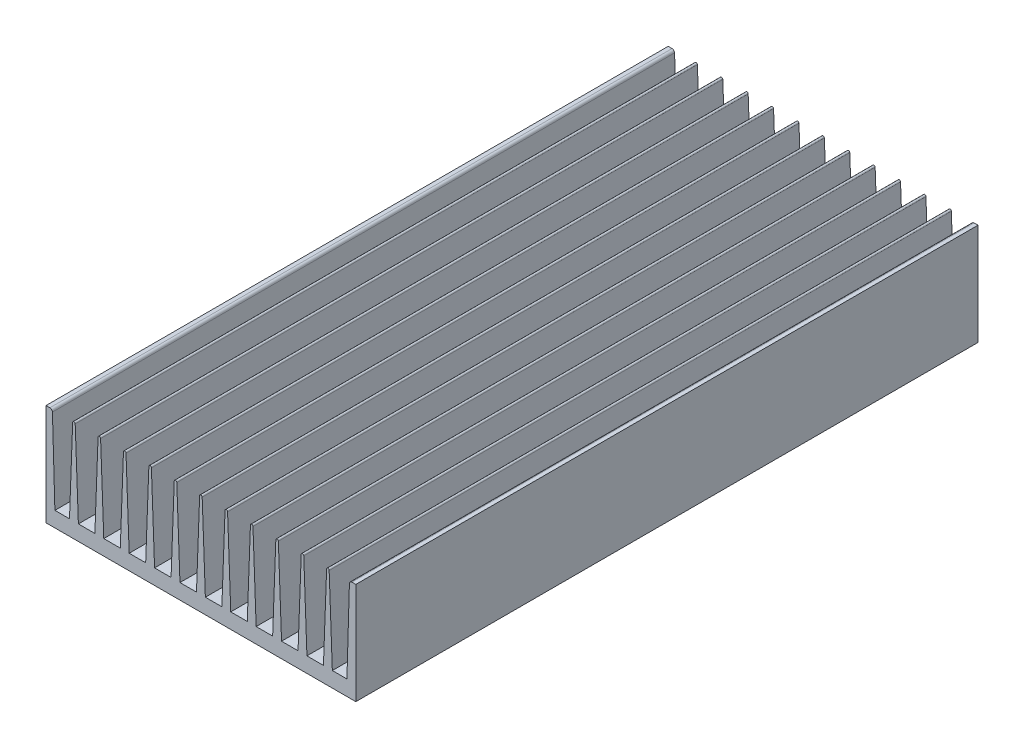
SolidWorks part; units mm, degrees
ref_plane "Спереди" through (0, 0, 0) normal (0, 0, 1) x (1, 0, 0)
ref_plane "Сверху" through (0, 0, 0) normal (0, 1, 0) x (1, 0, 0)
ref_plane "Справа" through (0, 0, 0) normal (1, 0, 0) x (0, 0, -1)
sketch "Эскиз1" plane through (0, 0, 0) normal (0, 0, 1) x (1, 0, 0)
  line L0 (0, 40) -> (1.529, 40)
  line L1 (0, 0) -> (122, 0)
  line L2 (2.5285, 39.0294) -> (3.5, 6)
  line L3 (0, 40) -> (0, 0)
  line L4 (122, 40) -> (122, 0)
  line L5 (61, 63.7127) -> (61, -22.2582) construction
  line L8 (122, 40) -> (120.471, 40)
  line L9 (119.4715, 39.0294) -> (118.5, 6)
  line L10 (3.5, 6) -> (118.5, 6)
  arc A0 (1.529, 40) -> (2.5285, 39.0294) centre (1.529, 39) cw
  arc A2 (120.471, 40) -> (119.4715, 39.0294) centre (120.471, 39) ccw
  point P18 (119.5, 40)
  dimension "D9" = 1
  dimension "D1" = 122
  dimension "D2" = 6
  dimension "D3" = 40
  dimension "D4" = 3.5
  dimension "D7" = 2.5
extrude "Вытянуть1" add sketch "Эскиз1" along normal blind 245
sketch "Эскиз2" plane through (0, 0, 245) normal (0, 0, 1) x (1, 0, 0)
  line L0 (118.5, 6) -> (3.5, 6) construction
  line L1 (10.5, 39.5) -> (9.25, 6)
  line L2 (11, 39.5) -> (11, 22.5548) construction
  line L3 (11.5, 39.5) -> (12.75, 6)
  line L4 (9.25, 6) -> (12.75, 6)
  line L6 (0, 40) -> (0, 0) construction
  arc A0 (10.5, 39.5) -> (11.5, 39.5) centre (11, 39.5) cw
  dimension "D1" = 34
  dimension "D3" = 0.5
  dimension "D2" = 3.5
  dimension "D4" = 11
  dimension "D5" = 1
extrude "Вытянуть3" add sketch "Эскиз2" against normal blind 245
pattern_curve "Кривая1" of "Вытянуть3" along edge at (61, 0, 0) parameters "D1"=11, "D3"=10, "D2"=1, "D4"=50
sketch "Эскиз3" plane through (0, 0, 0) normal (0, -1, 0) x (1, 0, 0)
  line L0 (-14.0506, 236.5) -> (137.5079, 236.5) construction
  line L1 (0, 245) -> (122, 245) construction
  line L2 (0, 245) -> (0, 0) construction
  line L3 (-46.7511, 122.5) -> (151.4312, 122.5) construction
  line L4 (0, 0) -> (122, 0) construction
  circle A0 centre (22, 236.5) radius 1.6
  circle A1 centre (102, 236.5) radius 1.6
  circle A2 centre (102, 8.5) radius 1.6
  circle A3 centre (22, 8.5) radius 1.6
  dimension "D2" = 80
  dimension "D4" = 3.2
  dimension "D1" = 8.5
  dimension "D3" = 22
extrude "Вырез-Вытянуть1" cut sketch "Эскиз3" against normal blind 6
cosmetic thread "Условное изображение резьбы1" parameters "D2"=4
cosmetic thread "Условное изображение резьбы2" parameters "D2"=4
cosmetic thread "Условное изображение резьбы3" parameters "D2"=4
cosmetic thread "Условное изображение резьбы4" parameters "D2"=4
